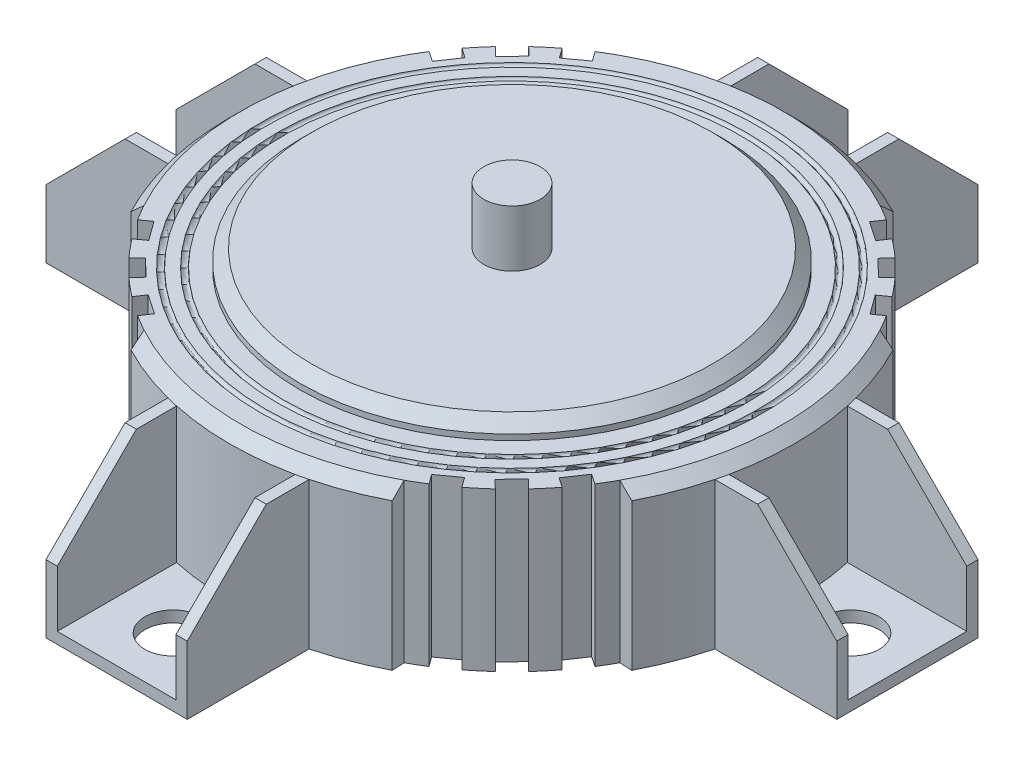
SolidWorks part; units mm, degrees
ref_plane "Front Plane" through (0, 0, 0) normal (0, 0, 1) x (1, 0, 0)
ref_plane "Top Plane" through (0, 0, 0) normal (0, 1, 0) x (1, 0, 0)
ref_plane "Right Plane" through (0, 0, 0) normal (1, 0, 0) x (0, 0, -1)
sketch "Sketch1" plane through (0, 0, 0) normal (0, 0, 1) x (1, 0, 0)
  line L0 (0, 0) -> (0, 41) construction
  line L1 (0, 0) -> (-50, 0)
  line L2 (-50, 0) -> (-50, 28)
  line L3 (-50, 28) -> (-37.5, 28)
  line L4 (-37.5, 28) -> (-37.5, 31)
  line L5 (-37.5, 31) -> (-5, 31)
  line L6 (-5, 31) -> (-5, 41)
  line L7 (-5, 41) -> (0, 41)
  line L8 (0, 0) -> (0, 41)
  point P5 (0, 0)
  point P10 (-39.8124, 56)
  point P11 (-11.5088, 37.6308)
  dimension "D1" = 28
  dimension "D2" = 3
  dimension "D3" = 10
  dimension "D4" = 100
  dimension "D5" = 10
  dimension "D6" = 75
revolve "Revolve1" add sketch "Sketch1" angle 360 about L0
chamfer "Chamfer1" distance 2 angle 45 2 edges at (0, 31, -37.5) (0, 28, -50)
sketch "Sketch2" plane through (0, 0, 0) normal (0, 0, 1) x (1, 0, 0)
  line L0 (0, 0) -> (0, 26.5178) construction
  line L1 (-50, 0) -> (50, 0) construction
  line L2 (12.5, 0) -> (-12.5, 0)
  line L3 (-12.5, 0) -> (-12.5, 26)
  line L4 (50, 26) -> (-50, 26) construction
  line L5 (-12.5, 26) -> (-10.5, 26)
  line L6 (-10.5, 26) -> (-10.5, 2)
  line L7 (-10.5, 2) -> (10.5, 2)
  line L8 (12.5, 26) -> (10.5, 26)
  line L9 (12.5, 0) -> (12.5, 26)
  line L10 (10.5, 26) -> (10.5, 2)
  point P10 (-9.1532, 26)
  point P14 (0, 2)
  dimension "D1" = 25
  dimension "D2" = 2
  dimension "D3" = 2
extrude "Boss-Extrude1" add sketch "Sketch2" along normal blind 70
chamfer "Chamfer2" distance 14 angle 45 2 edges at (11.5, 26, 70) (-11.5, 26, 70)
sketch "Sketch3" plane through (0, 31, 0) normal (0, 1, 0) x (1, 0, 0)
  line L0 (0, 0) -> (0, -60) construction
  circle A0 centre (0, -60) radius 5
  dimension "D1" = 10
  dimension "D2" = 60
extrude "Cut-Extrude1" cut sketch "Sketch3" against normal blind 70
pattern_circular "CirPattern1" count 4 over 360 about axis through (0, 0, 0) along (0, 1, 0) of "Boss-Extrude1", "Chamfer2", "Cut-Extrude1"
sketch "Sketch4" plane through (0, 0, 0) normal (0, 1, 0) x (1, 0, 0)
  line L0 (0, 0) -> (35.3553, -35.3553) construction
  line L1 (23.0251, -42.117) -> (23.1202, -44.3334)
  line L2 (42.117, -23.0251) -> (44.3334, -23.1202)
  arc A0 (12.5, -48.4123) -> (48.4123, -12.5) centre (0, 0) ccw construction
  circle A1 centre (0, 0) radius 48 construction
  arc A2 (23.1202, -44.3334) -> (44.3334, -23.1202) centre (0, 0) ccw
  arc A3 (23.0251, -42.117) -> (42.117, -23.0251) centre (0, 0) ccw
  dimension "D1" = 30
  dimension "D2" = 27
extrude "Cut-Extrude2" cut sketch "Sketch4" along normal blind 70
sketch "Sketch5" plane through (0, 0, 0) normal (0, 1, 0) x (1, 0, 0)
  line L0 (-0.2432, -0.7995) -> (33.9411, -33.9411) construction
  line L5 (30.9397, -33.9411) -> (34.0341, -36.9411)
  line L6 (30.9397, -33.9411) -> (33.8482, -30.9411)
  line L7 (34.0341, -36.9411) -> (36.9426, -33.9411)
  line L8 (33.8482, -30.9411) -> (36.9426, -33.9411)
  line L9 (35.4883, -35.4411) -> (32.3939, -32.4411) construction
  line L10 (32.4869, -35.4411) -> (35.3954, -32.4411) construction
  arc A1 (23.0251, -42.117) -> (42.117, -23.0251) centre (0, 0) ccw construction
  point P2 (0, 0)
  point P3 (0, 0)
  point P6 (0, 0)
  point P8 (0, 0)
  point P10 (33.9411, -33.9411)
  dimension "D1" = 3
  dimension "D2" = 3
extrude "Cut-Extrude3" cut sketch "Sketch5" along normal blind 70
pattern_circular "CirPattern2" count 2 every 10 about axis through (0, 0, 0) along (0, 1, 0) of "Cut-Extrude3"
pattern_circular "CirPattern3" count 4 over 360 about axis through (0, 0, 0) along (0, 1, 0) of "CirPattern2", "Cut-Extrude3", "Cut-Extrude2"
sketch "Sketch14" plane through (0, 28, 0) normal (0, 1, 0) x (1, 0, 0)
  circle A0 centre (0, 0) radius 41
  dimension "D1" = 82
sketch "Sketch15" plane through (0, 28, 0) normal (0, 1, 0) x (1, 0, 0)
  circle A0 centre (0, 0) radius 44
  dimension "D1" = 88
sweep "Cut-Sweep2" cut path "Sketch15" circular profile diameter 1 parameters "D3"=1
sweep "Cut-Sweep3" cut path "Sketch14" circular profile diameter 1 parameters "D3"=1
sketch "Sketch27" plane through (0, 0, 0) normal (0, -1, 0) x (1, 0, 0)
  circle A0 centre (0, 0) radius 37.5
  dimension "D1" = 75
extrude "Cut-Extrude4" cut sketch "Sketch27" against normal blind 10
